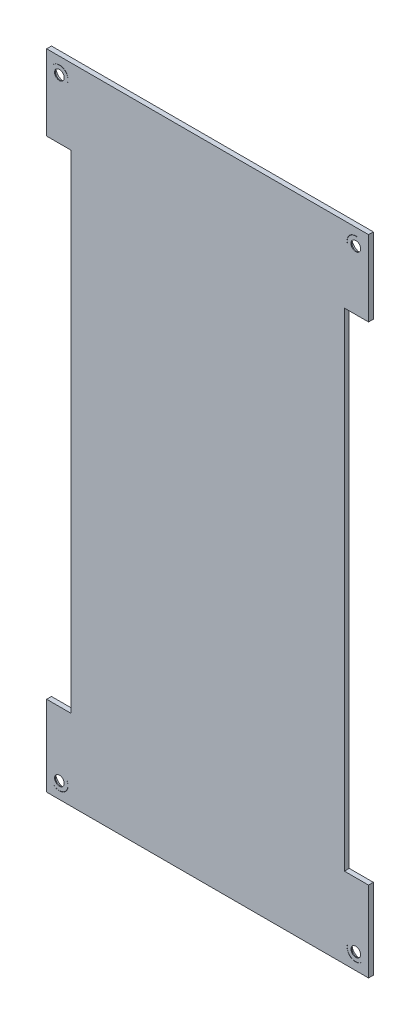
SolidWorks part; units mm, degrees
ref_plane "Front Plane" through (0, 0, 0) normal (0, 0, 1) x (1, 0, 0)
ref_plane "Top Plane" through (0, 0, 0) normal (0, 1, 0) x (1, 0, 0)
ref_plane "Right Plane" through (0, 0, 0) normal (1, 0, 0) x (0, 0, -1)
sketch "Sketch2" plane through (0, 0, 0) normal (0, 0, 1) x (1, 0, 0)
  line L8 (3, 200) -> (-5.559, 200) construction
  line L9 (0, 197) -> (0, 179.9048) construction
  line L10 (100, 3) -> (100, 0) construction
  line L11 (100, 0) -> (53, 0) construction
  line L13 (0, 200) -> (100, 200)
  line L14 (0, 200) -> (0, 0)
  line L15 (0, 0) -> (100, 0)
  line L16 (100, 200) -> (100, 0)
  point P0 (0, 0)
  point P1 (56, 200)
  point P2 (0, 200)
  dimension "D1" = 56
  dimension "D2" = 200
  dimension "D3" = 100
extrude "Boss-Extrude1" add sketch "Sketch2" along normal blind 1.5
sketch "Sketch4" plane through (0, 0, 1.5) normal (0, 0, 1) x (1, 0, 0)
  line L2 (50, 200) -> (50, 0) construction
  line L4 (0, 0) -> (100, 0) construction
  line L6 (100, 200) -> (0, 200) construction
  line L7 (0, 200) -> (0, 0) construction
  line L8 (0, 100) -> (100, 100) construction
  line L9 (100, 0) -> (100, 200) construction
  circle A0 centre (4, 195) radius 2.667
  circle A4 centre (96, 195) radius 2.667
  circle A5 centre (96, 5) radius 2.667
  circle A6 centre (4, 5) radius 2.667
  dimension "D1" = 5
  dimension "D2" = 4
extrude "Cut-Extrude1" cut sketch "Sketch4" against normal blind 2
sketch "Sketch5" plane through (0, 0, 1.5) normal (0, 0, 1) x (1, 0, 0)
  line L0 (50, 200) -> (50, 0) construction
  line L3 (100, 200) -> (0, 200) construction
  line L6 (0, 0) -> (100, 0) construction
  line L7 (0, 100) -> (100, 100) construction
  line L8 (0, 200) -> (0, 0) construction
  line L9 (100, 0) -> (100, 200) construction
  circle A6 centre (3.9597, 5.0688) radius 2.667
  circle A7 centre (3.9597, 5.0688) radius 1.5
  circle A8 centre (3.9597, 194.9312) radius 1.5
  circle A9 centre (3.9597, 194.9312) radius 2.667
  circle A10 centre (96.0403, 5.0688) radius 1.5
  circle A11 centre (96.0403, 5.0688) radius 2.667
  circle A12 centre (96.0403, 194.9312) radius 2.667
  circle A13 centre (96.0403, 194.9312) radius 1.5
extrude "Boss-Extrude2" add sketch "Sketch5" against normal blind 0.254
sketch "Sketch6" plane through (0, 0, 0) normal (0, 0, 1) x (1, 0, 0)
  line L0 (50, 0) -> (50, 132.7004) construction
  line L1 (0, 200) -> (0, 0) construction
  line L2 (0, 25) -> (7.5, 25)
  line L3 (7.5, 25) -> (7.5, 175)
  line L4 (7.5, 175) -> (0, 175)
  line L6 (0, 0) -> (100, 0) construction
  line L8 (0, 25) -> (0, 175)
  line L9 (100, 25) -> (92.5, 25)
  line L10 (92.5, 25) -> (92.5, 175)
  line L11 (92.5, 175) -> (100, 175)
  line L12 (100, 25) -> (100, 175)
extrude "Cut-Extrude2" cut sketch "Sketch6" along normal blind 1.5 contours L9 L10 L11 L12 | L8 L4 L3 L2
sketch "Sketch7" plane through (0, 175, 0) normal (0, -1, 0) x (1, 0, 0)
  line L4 (0, 0) -> (7.5, 0)
  line L5 (7.5, 0) -> (7.5, 1.5)
  line L6 (7.5, 1.5) -> (0, 1.5)
  line L7 (0, 1.5) -> (0, 0)
  line L8 (0, 0) -> (7.5, 0)
  line L9 (7.5, 0) -> (7.5, 1.5)
  line L10 (7.5, 1.5) -> (0, 1.5)
  line L11 (0, 1.5) -> (0, 0)
  line L12 (92.5, 0) -> (100, 0)
  line L13 (100, 0) -> (100, 1.5)
  line L14 (100, 1.5) -> (92.5, 1.5)
  line L15 (92.5, 1.5) -> (92.5, 0)
  line L16 (92.5, 0) -> (100, 0)
  line L17 (100, 0) -> (100, 1.5)
  line L18 (100, 1.5) -> (92.5, 1.5)
  line L19 (92.5, 1.5) -> (92.5, 0)
  dimension "D1" = 0
  dimension "D2" = 0
extrude "Cut-Extrude3" cut sketch "Sketch7" against normal blind 1.5
